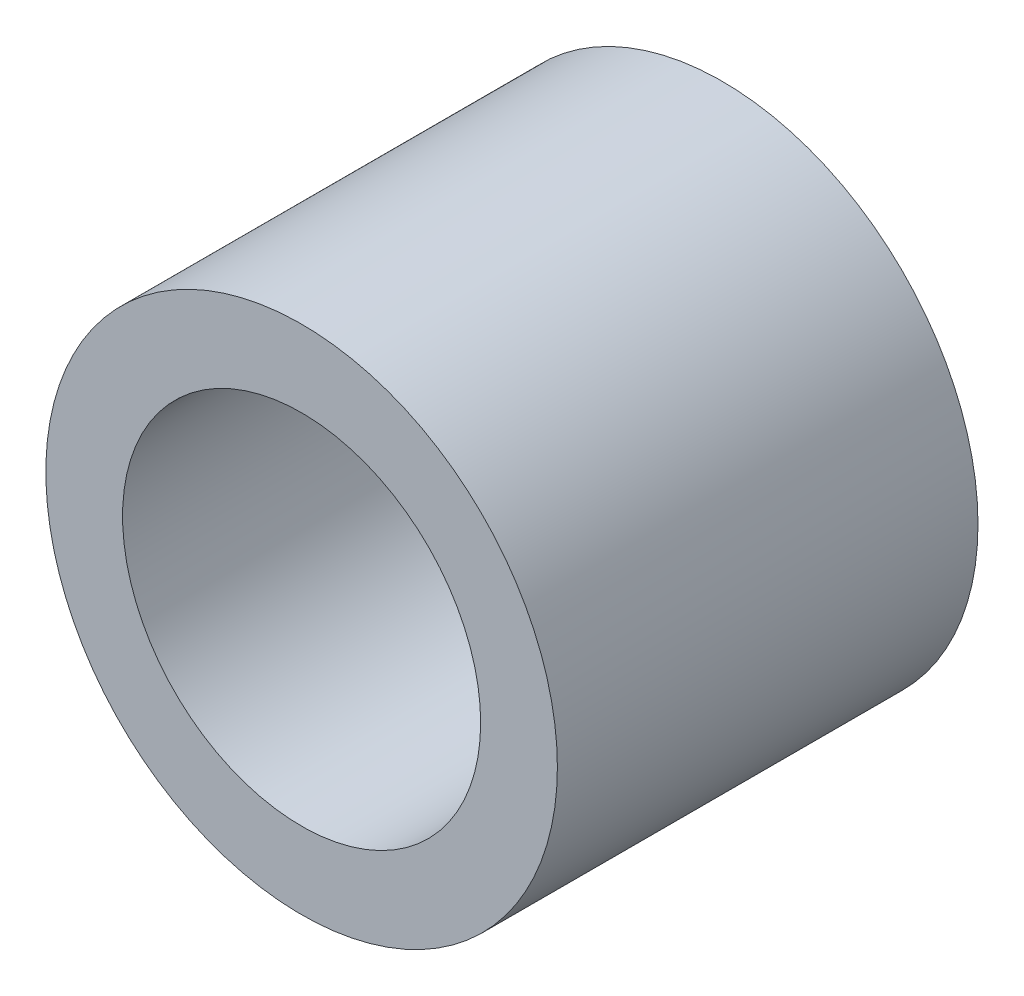
SolidWorks part; units mm, degrees
ref_plane "Front Plane" through (0, 0, 0) normal (1, 0, 0) x (0, 1, 0)
ref_plane "Top Plane" through (0, 0, 0) normal (0, 0, 1) x (0, 1, 0)
ref_plane "Right Plane" through (0, 0, 0) normal (0, 1, 0) x (-1, 0, 0)
sketch "Sketch1" plane through (0, 0, 0) normal (0, 0, 1) x (0, 1, 0)
  circle A0 centre (0, 0) radius 3.15
  circle A1 centre (0, 0) radius 4.5
  dimension "D1" = 6.3
  dimension "D2" = 9
extrude "Boss-Extrude1" add sketch "Sketch1" along normal blind 7.4
